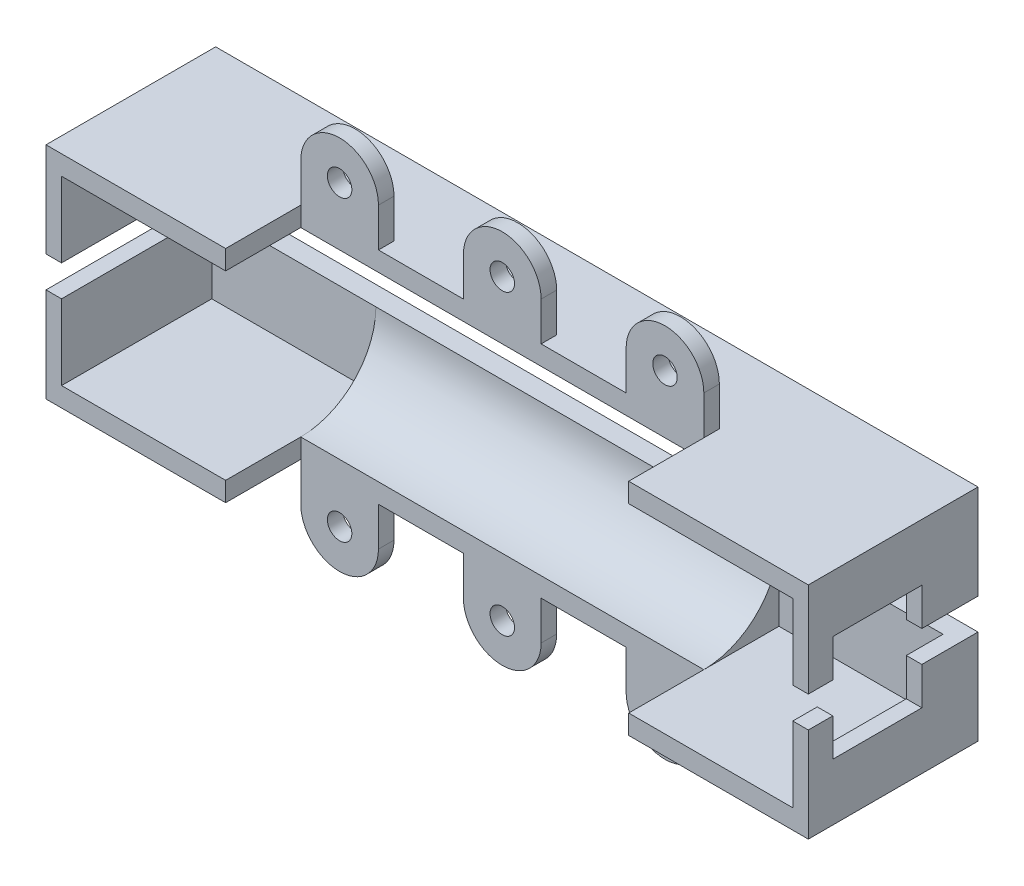
SolidWorks part; units mm, degrees
material "ABS"
ref_plane "X-Y Datum" through (0, 0, 0) normal (0, 0, 1) x (1, 0, 0)
ref_plane "X-Z Datum" through (0, 0, 0) normal (0, 1, 0) x (1, 0, 0)
ref_plane "Y-Z Datum" through (0, 0, 0) normal (1, 0, 0) x (0, 0, -1)
sketch "Sketch1" plane through (0, 0, 0) normal (1, 0, 0) x (0, 0, -1)
  line L1 (34.2074, 10.3366) -> (37.3824, 10.3366)
  line L4 (37.3824, 10.3366) -> (37.3824, -5.1193)
  line L5 (37.3824, -5.1193) -> (21.9265, -5.1193)
  line L6 (21.9265, -5.1193) -> (21.9265, -1.9443)
  arc A0 (21.9265, -1.9443) -> (34.2074, 10.3366) centre (21.9265, 10.3366) ccw
extrude "Boss-Extrude1" add sketch "Sketch1" along normal blind 65.8876
sketch "Sketch2" plane through (65.8876, 0, 0) normal (1, 0, 0) x (0, 0, -1)
  line L0 (37.3824, -1.9443) -> (37.3824, 10.3366)
  line L1 (37.3824, -5.1193) -> (9.6464, -5.1193)
  line L2 (37.3824, -5.1193) -> (37.3824, -1.9443)
  line L3 (34.2074, -1.9443) -> (9.6464, -1.9443)
  line L4 (9.6464, -5.1193) -> (9.6464, -1.9443)
  line L5 (37.3824, 10.3366) -> (34.2074, 10.3366)
  line L6 (34.2074, 10.3366) -> (34.2074, -1.9443)
extrude "Boss-Extrude2" add sketch "Sketch2" along normal blind 29.3624
sketch "Sketch3" plane through (95.25, 0, 0) normal (1, 0, 0) x (0, 0, -1)
  line L0 (28.2074, 4.1961) -> (13.6464, 4.1961)
  line L1 (34.2074, -1.9443) -> (28.2074, -1.9443)
  line L2 (34.2074, -1.9443) -> (34.2074, 10.3366)
  line L3 (34.2074, 10.3366) -> (28.2074, 10.3366)
  line L4 (28.2074, 4.1961) -> (28.2074, 10.3366)
  line L5 (9.6464, 4.1961) -> (9.6464, -1.9443)
  line L6 (9.6464, -1.9443) -> (28.2074, -1.9443)
  line L7 (9.6464, 4.1961) -> (9.6464, 10.3366)
  line L8 (9.6464, 10.3366) -> (13.6464, 10.3366)
  line L9 (13.6464, 10.3366) -> (13.6464, 4.1961)
extrude "Boss-Extrude3" add sketch "Sketch3" against normal blind 2.54
sketch "Sketch4" plane through (0, 0, -21.9265) normal (0, 0, 1) x (1, 0, 0)
  line L1 (0, -11.4693) -> (0, -5.1193)
  line L4 (12.7, -11.4693) -> (12.7, -5.1193)
  line L10 (12.7, -5.1193) -> (0, -5.1193)
  line L12 (32.9438, -5.1193) -> (32.9438, -11.4693) construction
  line L13 (26.5938, -11.4693) -> (26.5938, -5.1193)
  line L23 (0, -5.1193) -> (3.175, -5.1193) construction
  line L24 (65.8876, -5.1193) -> (0, -5.1193) construction
  line L25 (39.2938, -11.4693) -> (39.2938, -5.1193)
  line L26 (39.2938, -5.1193) -> (26.5938, -5.1193)
  line L27 (65.8876, -5.1193) -> (62.7126, -5.1193) construction
  line L28 (53.1876, -5.1193) -> (65.8876, -5.1193)
  line L29 (53.1876, -11.4693) -> (53.1876, -5.1193)
  line L30 (65.8876, -11.4693) -> (65.8876, -5.1193)
  arc A12 (0, -11.4693) -> (12.7, -11.4693) centre (6.35, -11.4693) ccw
  arc A13 (26.5938, -11.4693) -> (39.2938, -11.4693) centre (32.9438, -11.4693) ccw
  circle A14 centre (6.35, -11.4693) radius 2
  circle A15 centre (32.9438, -11.4693) radius 2
  circle A16 centre (59.5376, -11.4693) radius 2
  arc A17 (65.8876, -11.4693) -> (53.1876, -11.4693) centre (59.5376, -11.4693) cw
extrude "Boss-Extrude4" add sketch "Sketch4" against normal blind 2.54
ref_plane "Plane1" through (32.9438, 0, 0) normal (1, 0, 0) x (0, 0, -1)
mirror "Mirror1" about plane through (32.9438, 0, 0) normal (1, 0, 0) of "Boss-Extrude2"
sketch "Sketch6" plane through (-29.3624, 0, 0) normal (-1, 0, 0) x (0, 0, 1)
  line L0 (-9.6464, 10.3366) -> (-9.6464, -1.9443) construction
  line L1 (-34.2074, -1.9443) -> (-9.6464, -1.9443)
  line L2 (-34.2074, -1.9443) -> (-34.2074, 10.3366)
  line L3 (-34.2074, 10.3366) -> (-9.6464, 10.3366)
  line L4 (-9.6464, -1.9443) -> (-9.6464, 10.3366)
  line L5 (-13.6464, 10.3366) -> (-9.6464, 10.3366) construction
extrude "Boss-Extrude5" add sketch "Sketch6" against normal blind 2.54
ref_plane "Plane2" through (0, 12.8766, 0) normal (0, 1, 0) x (1, 0, 0)
mirror "Mirror3" about plane through (0, 12.8766, 0) normal (0, 1, 0) of bodies 106
